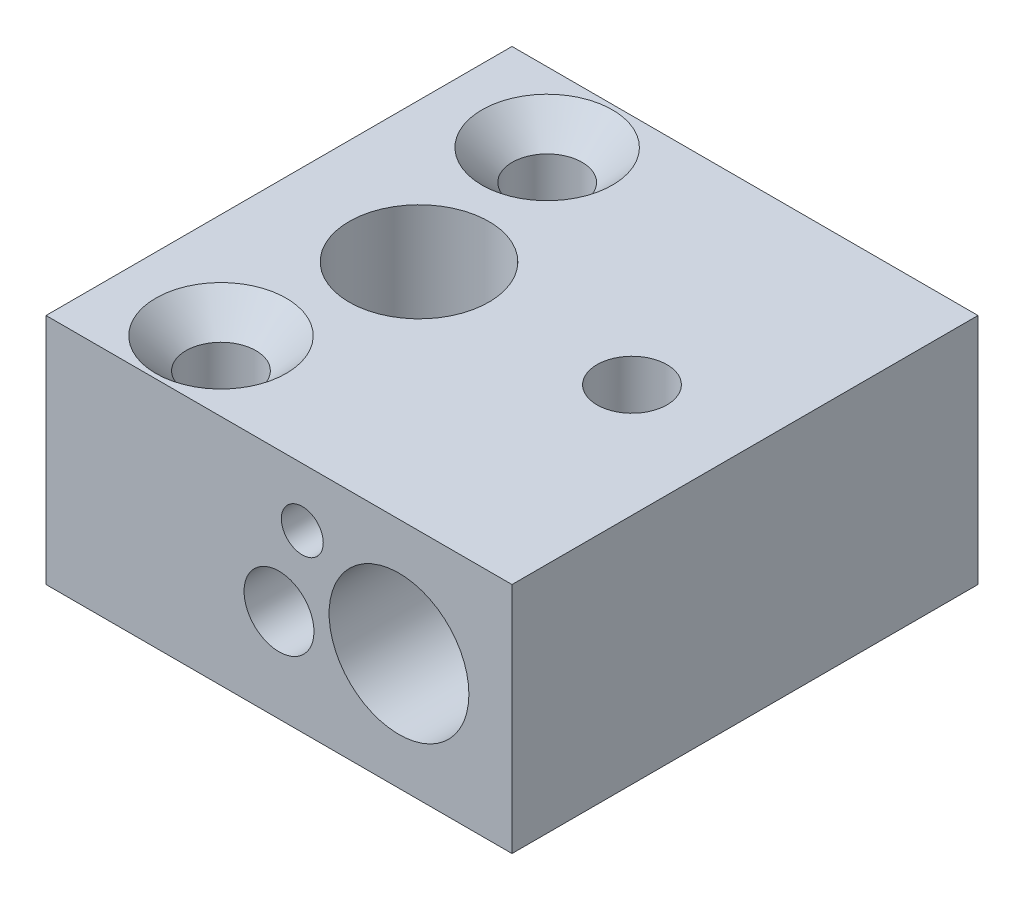
SolidWorks part; units mm, degrees
ref_plane "Płaszczyzna przednia" through (0, 0, 0) normal (0, 0, 1) x (1, 0, 0)
ref_plane "Płaszczyzna górna" through (0, 0, 0) normal (0, 1, 0) x (1, 0, 0)
ref_plane "Płaszczyzna prawa" through (0, 0, 0) normal (1, 0, 0) x (0, 0, -1)
sketch "Sketch1" plane through (0, 0, 0) normal (0, 1, 0) x (1, 0, 0)
  line L1 (0, 0) -> (20, 0)
  line L2 (0, 0) -> (0, 20)
  line L3 (0, 20) -> (20, 20)
  line L4 (20, 0) -> (20, 20)
  dimension "D1" = 20
  dimension "D2" = 20
extrude "Boss-Extrude1" add sketch "Sketch1" along normal blind 10
hole_wizard "Ø6.0mm Dowel Hole2" positions "Sketch2" profile "Sketch3" hole size "Ø6.0" standard "ANSI Metric" end condition through all
sketch "Sketch2" plane through (0, 10, 0) normal (0, 1, 0) x (1, 0, 0)
  line L0 (0, 20) -> (0, 0) construction
  line L2 (0, 0) -> (20, 0) construction
  point P0 (6.01, 10)
  dimension "D1" = 6.01
  dimension "D2" = 10
sketch "Sketch3" plane through (6.01, 10, -10) normal (1, 0, 0) x (0, 0, 1)
  line L0 (0, 0) -> (0, 10)
  line L1 (0, 10) -> (3, 10)
  line L2 (3, 10) -> (3, 0)
  line L5 (3, 0) -> (0, 0)
  line L11 (0, -6.35) -> (0, 107.95) construction
  dimension "Thru Hole Dia." = 6
  dimension "Thru Hole Depth" = 10
hole_wizard "CSK for M3 Flat Head Machine Screw1" positions "Sketch4" profile "Sketch5" countersink size "M3" standard "ANSI Metric" end condition through all
sketch "Sketch4" plane through (0, 10, 0) normal (0, 1, 0) x (1, 0, 0)
  line L1 (0, 0) -> (20, 0) construction
  circle A1 centre (6.01, 10) radius 3 construction
  point P0 (4.51, 3)
  point P2 (4.51, 17)
  dimension "D1" = 1.5
  dimension "D2" = 14
  dimension "D3" = 3
sketch "Sketch5" plane through (4.51, 10, -3) normal (1, 0, 0) x (0, 0, 1)
  line L0 (0, 0) -> (0, 10)
  line L1 (0, 10) -> (1.5, 10)
  line L2 (1.5, 10) -> (1.5, 1.3)
  line L3 (1.5, 1.3) -> (2.8, 0)
  line L5 (2.8, 0) -> (0, 0)
  line L6 (-1.5, 1.3) -> (-2.8, 0) construction
  line L11 (0, -6.35) -> (0, 107.95) construction
  dimension "Thru Hole Dia." = 3
  dimension "Thru Hole Depth" = 10
  dimension "Near C'Sink Dia." = 5.6
  dimension "Near C'Sink Angle" = 90
hole_wizard "Ø6.0mm Dowel Hole3" positions "Sketch6" profile "Sketch8" hole size "Ø6.0" standard "ANSI Metric" end condition through all
sketch "Sketch6" plane through (0, 0, 0) normal (0, 0, 1) x (1, 0, 0)
  line L0 (0, 10) -> (20, 10) construction
  line L2 (20, 10) -> (20, 0) construction
  point P0 (15.15, 5)
  dimension "D1" = 5
  dimension "D2" = 4.85
sketch "Sketch8" plane through (15.15, 5, 0) normal (1, 0, 0) x (0, -1, 0)
  line L0 (0, 0) -> (0, 20)
  line L1 (0, 20) -> (3, 20)
  line L2 (3, 20) -> (3, 0)
  line L5 (3, 0) -> (0, 0)
  line L11 (0, -6.35) -> (0, 107.95) construction
  dimension "Thru Hole Dia." = 6
  dimension "Thru Hole Depth" = 20
hole_wizard "Ø3.0mm Dowel Hole1" positions "Sketch9" profile "Sketch10" hole size "Ø3.0" standard "ANSI Metric"
sketch "Sketch9" plane through (0, 10, 0) normal (0, 1, 0) x (1, 0, 0)
  line L0 (20, 0) -> (20, 20) construction
  line L1 (0, 0) -> (20, 0) construction
  point P0 (15.15, 10)
  dimension "D1" = 4.85
  dimension "D2" = 10
sketch "Sketch10" plane through (15.15, 10, -10) normal (1, 0, 0) x (0, 0, 1)
  line L0 (0, 0) -> (0, 2)
  line L1 (0, 2) -> (1.5, 2)
  line L2 (1.5, 2) -> (1.5, 0)
  line L5 (1.5, 0) -> (0, 0)
  line L11 (0, -6.35) -> (0, 107.95) construction
  dimension "Thru Hole Dia." = 3
  dimension "Thru Hole Depth" = 2
hole_wizard "Ø3.0mm Dowel Hole2" positions "Sketch13" profile "Sketch14" hole size "Ø3.0" standard "ANSI Metric"
sketch "Sketch13" plane through (0, 0, 0) normal (0, 0, 1) x (1, 0, 0)
  line L0 (20, 10) -> (20, 0) construction
  circle A0 centre (15.15, 5) radius 3 construction
  point P0 (10, 4)
  dimension "D1" = 1
  dimension "D2" = 10
sketch "Sketch14" plane through (10, 4, 0) normal (1, 0, 0) x (0, -1, 0)
  line L0 (0, 0) -> (0, 6.9013)
  line L1 (0, 6.9013) -> (1.5, 6)
  line L2 (1.5, 6) -> (1.5, 0)
  line L5 (1.5, 0) -> (0, 0)
  line L10 (0, 6.9013) -> (-1.5, 6) construction
  line L11 (0, -6.35) -> (0, 107.95) construction
  dimension "Hole Dia." = 3
  dimension "Hole Depth" = 6
  dimension "Drill Angle" = 118
hole_wizard "Ø1.5mm Dowel Hole1" positions "Sketch15" profile "Sketch16" hole size "Ø1.5" standard "ANSI Metric"
sketch "Sketch15" plane through (0, 0, 0) normal (0, 0, 1) x (1, 0, 0)
  line L0 (20, 10) -> (20, 0) construction
  line L1 (0, 10) -> (20, 10) construction
  point P0 (11, 7.5)
  dimension "D1" = 9
  dimension "D2" = 2.5
sketch "Sketch16" plane through (11, 7.5, 0) normal (1, 0, 0) x (0, -1, 0)
  line L0 (0, 0) -> (0, 4.5408)
  line L1 (0, 4.5408) -> (0.9, 4)
  line L2 (0.9, 4) -> (0.9, 0)
  line L5 (0.9, 0) -> (0, 0)
  line L10 (0, 4.5408) -> (-0.9, 4) construction
  line L11 (0, -6.35) -> (0, 107.95) construction
  dimension "Hole Dia." = 1.8
  dimension "Hole Depth" = 4
  dimension "Drill Angle" = 118
